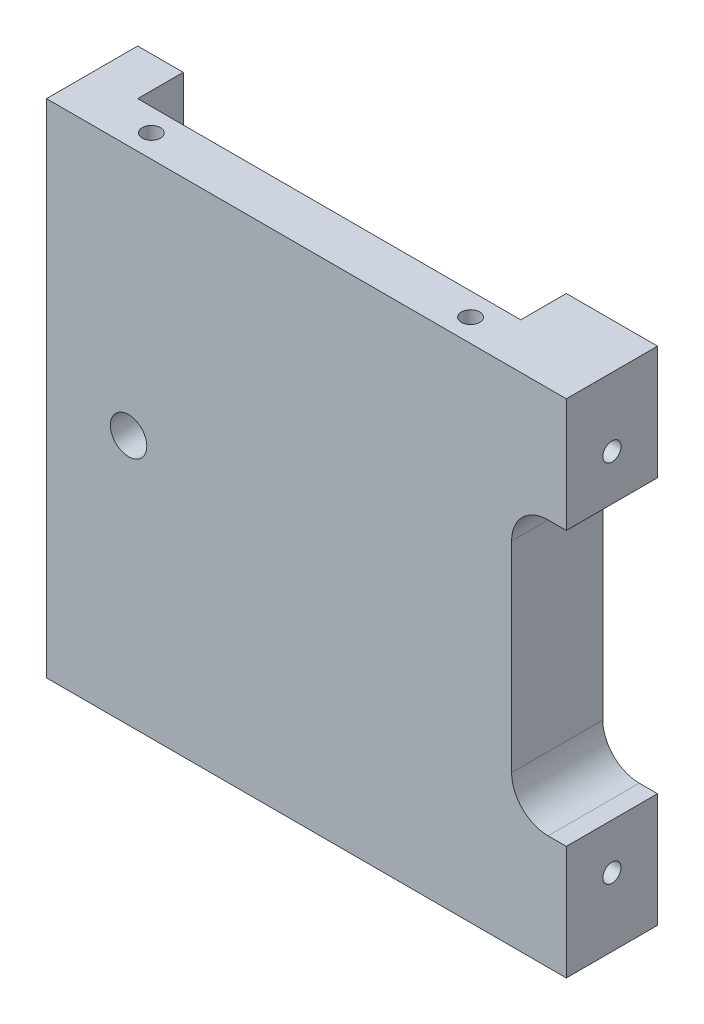
SolidWorks part; units mm, degrees
material "PE haute densité"
ref_plane "Plan de face" through (0, 0, 0) normal (0, 0, 1) x (1, 0, 0)
ref_plane "Plan de dessus" through (0, 0, 0) normal (0, 1, 0) x (1, 0, 0)
ref_plane "Plan de droite" through (0, 0, 0) normal (1, 0, 0) x (0, 0, -1)
sketch "Esquisse1" plane through (0, 0, 0) normal (0, 0, 1) x (1, 0, 0)
  line L1 (0, -27.5) -> (85, -27.5)
  line L2 (0, -27.5) -> (0, 27.5)
  line L3 (0, 27.5) -> (85, 27.5)
  line L4 (85, -27.5) -> (85, 27.5)
  dimension "D1" = 55
  dimension "D2" = 85
extrude "Boss.-Extru.1" add sketch "Esquisse1" along normal blind 10
sketch "Esquisse2" plane through (0, 27.5, 0) normal (0, 1, 0) x (1, 0, 0)
  line L0 (85, 0) -> (0, 0) construction
  line L1 (0, 0) -> (8, 0)
  line L2 (0, 0) -> (0, -5)
  line L3 (0, -5) -> (8, -5)
  line L4 (8, 0) -> (8, -5)
  line L5 (33, 0) -> (75, 0)
  line L6 (33, 0) -> (33, -5)
  line L7 (33, -5) -> (75, -5)
  line L8 (75, 0) -> (75, -5)
  line L9 (85, -10) -> (0, -10) construction
  dimension "D1" = 5
  dimension "D2" = 8
  dimension "D3" = 25
  dimension "D4" = 42
extrude "Enlèv. mat.-Extru.1" cut sketch "Esquisse2" against normal through all
sketch "Esquisse3" plane through (0, 0, 10) normal (0, 0, 1) x (1, 0, 0)
  line L0 (0, 0) -> (4, 0) construction
  line L1 (0, 27.5) -> (0, -27.5) construction
  line L2 (4, 0) -> (37, 0) construction
  circle A0 centre (4, 0) radius 2
  circle A1 centre (37, 0) radius 2
  dimension "D1" = 33
  dimension "D2" = 4
  dimension "D3" = 4
extrude "Enlèv. mat.-Extru.2" cut sketch "Esquisse3" against normal through all
hole_wizard "Trou taraudé M3x0.51" positions "Esquisse5" profile "Esquisse4" tap size "M3x0.5" standard "Ansi Metric"
sketch "Esquisse5" plane through (0, -27.5, 0) normal (0, -1, 0) x (-1, 0, 0)
  line L0 (-4, -7.5) -> (-37, -7.5) construction
  line L1 (-37, -7.5) -> (-72, -7.5) construction
  line L3 (0, -10) -> (-85, -10) construction
  line L6 (0, -10) -> (0, -5) construction
  point P0 (-4, -7.5)
  point P2 (-37, -7.5)
  point P4 (-72, -7.5)
  dimension "D1" = 2.5
  dimension "D2" = 4
  dimension "D3" = 33
  dimension "D4" = 35
sketch "Esquisse4" plane through (4, -27.5, 7.5) normal (1, 0, 0) x (0, 0, -1)
  line L0 (0, 0) -> (0, 15.6009)
  line L1 (0, 15.6009) -> (1, 15)
  line L2 (1, 15) -> (1, 0)
  line L5 (1, 0) -> (0, 0)
  line L10 (0, 15.6009) -> (-1, 15) construction
  line L11 (0, -6.35) -> (0, 107.95) construction
  dimension "Diamètre du trou pour taraudage" = 2
  dimension "Profondeur du trou pour taraudage" = 15
  dimension "Angle de pointe" = 118
cosmetic thread "Filetage de perçage1" parameters "D1"=10, "D2"=3
cosmetic thread "Filetage de perçage2" parameters "D1"=10, "D2"=3
cosmetic thread "Filetage de perçage3" parameters "D1"=10, "D2"=3
mirror "Symétrie1" about plane through (0, 0, 0) normal (0, 1, 0) of "Trou taraudé M3x0.51"
hole_wizard "Trou taraudé M3x0.52" positions "Esquisse7" profile "Esquisse6" tap size "M3x0.5" standard "Ansi Metric"
sketch "Esquisse7" plane through (85, 0, 0) normal (1, 0, 0) x (0, 0, -1)
  line L0 (-5, 20) -> (-5, -20) construction
  line L2 (0, 0) -> (-10, 0) construction
  line L4 (-10, -27.5) -> (-10, 27.5) construction
  line L5 (0, -27.5) -> (0, 27.5) construction
  point P0 (-5, 20)
  point P2 (-5, -20)
  point P18 (-5, 0)
  dimension "D1" = 40
sketch "Esquisse6" plane through (85, 20, 5) normal (0, 1, 0) x (0, 0, -1)
  line L0 (0, 0) -> (0, 12.6009)
  line L1 (0, 12.6009) -> (1, 12)
  line L2 (1, 12) -> (1, 0)
  line L5 (1, 0) -> (0, 0)
  line L10 (0, 12.6009) -> (-1, 12) construction
  line L11 (0, -6.35) -> (0, 107.95) construction
  dimension "Diamètre du trou pour taraudage" = 2
  dimension "Profondeur du trou pour taraudage" = 12
  dimension "Angle de pointe" = 118
cosmetic thread "Filetage de perçage4" parameters "D1"=10, "D2"=3
cosmetic thread "Filetage de perçage5" parameters "D1"=10, "D2"=3
sketch "Esquisse8" plane through (0, -27.5, 0) normal (0, -1, 0) x (1, 0, 0)
  line L0 (8, 0) -> (33, 0) construction
  line L1 (0, 10) -> (28, 10)
  line L2 (0, 10) -> (0, 0)
  line L3 (0, 0) -> (28, 0)
  line L4 (28, 10) -> (28, 0)
  line L5 (33, 0) -> (33, 5) construction
  dimension "D1" = 5
extrude "Enlèv. mat.-Extru.3" cut sketch "Esquisse8" against normal through all
sketch "Esquisse9" plane through (0, 0, 10) normal (0, 0, 1) x (1, 0, 0)
  line L0 (85, -27.5) -> (85, 27.5) construction
  line L1 (85, -15) -> (79, -15)
  line L2 (85, -15) -> (85, 15)
  line L3 (85, 15) -> (79, 15)
  line L4 (79, -15) -> (79, 15)
  point P4 (85, 0)
  dimension "D1" = 30
  dimension "D2" = 6
extrude "Enlèv. mat.-Extru.4" cut sketch "Esquisse9" against normal through all
fillet "Congé1" radius 4 2 edges at (79, 15, 5) (79, -15, 5)
